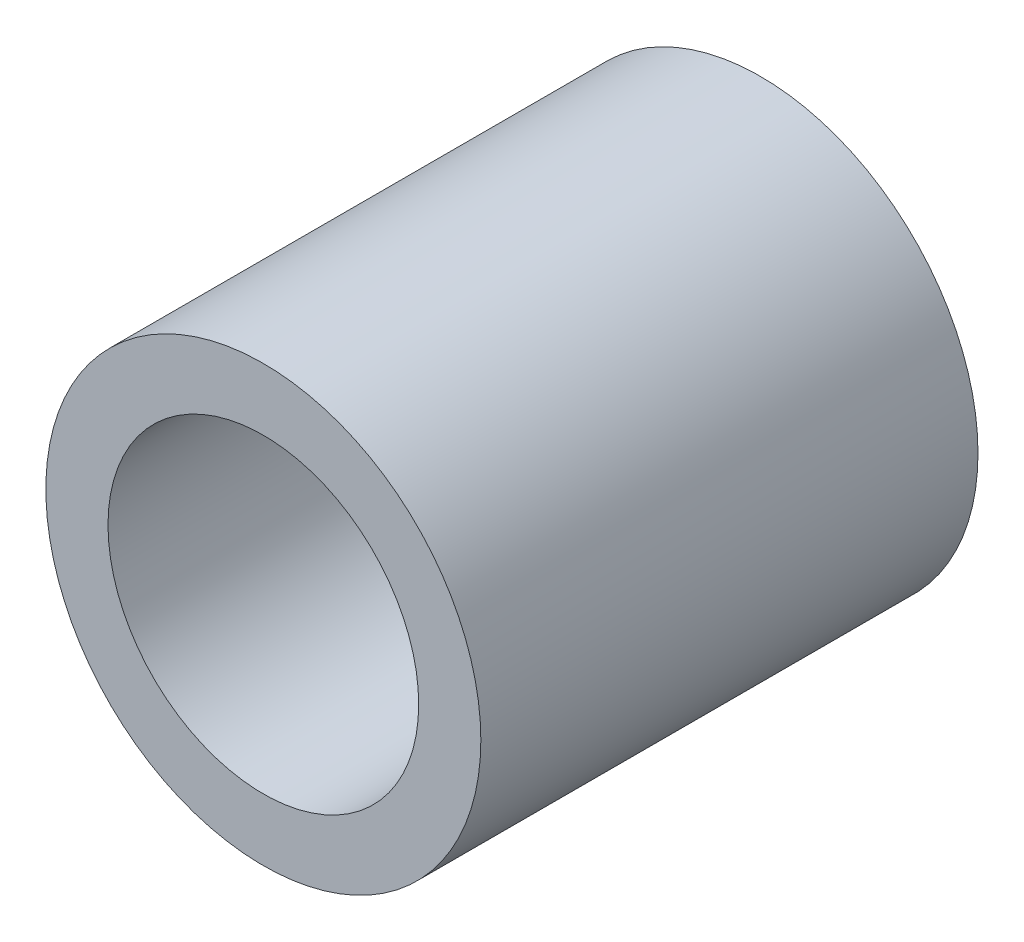
SolidWorks part; units mm, degrees
material "AISI 1020 Steel, Cold Rolled"
ref_plane "Front Plane" through (0, 0, 0) normal (0, 0, 1) x (1, 0, 0)
ref_plane "Top Plane" through (0, 0, 0) normal (0, 1, 0) x (1, 0, 0)
ref_plane "Right Plane" through (0, 0, 0) normal (1, 0, 0) x (0, 0, -1)
sketch "Sketch1" plane through (0, 0, 0) normal (0, 0, 1) x (1, 0, 0)
  circle A0 centre (0, 0) radius 7.9375
  circle A1 centre (0, 0) radius 11.1125
  dimension "D1" = 15.875
  dimension "D2" = 22.225
extrude "Boss-Extrude1" add sketch "Sketch1" along normal blind 25.4
